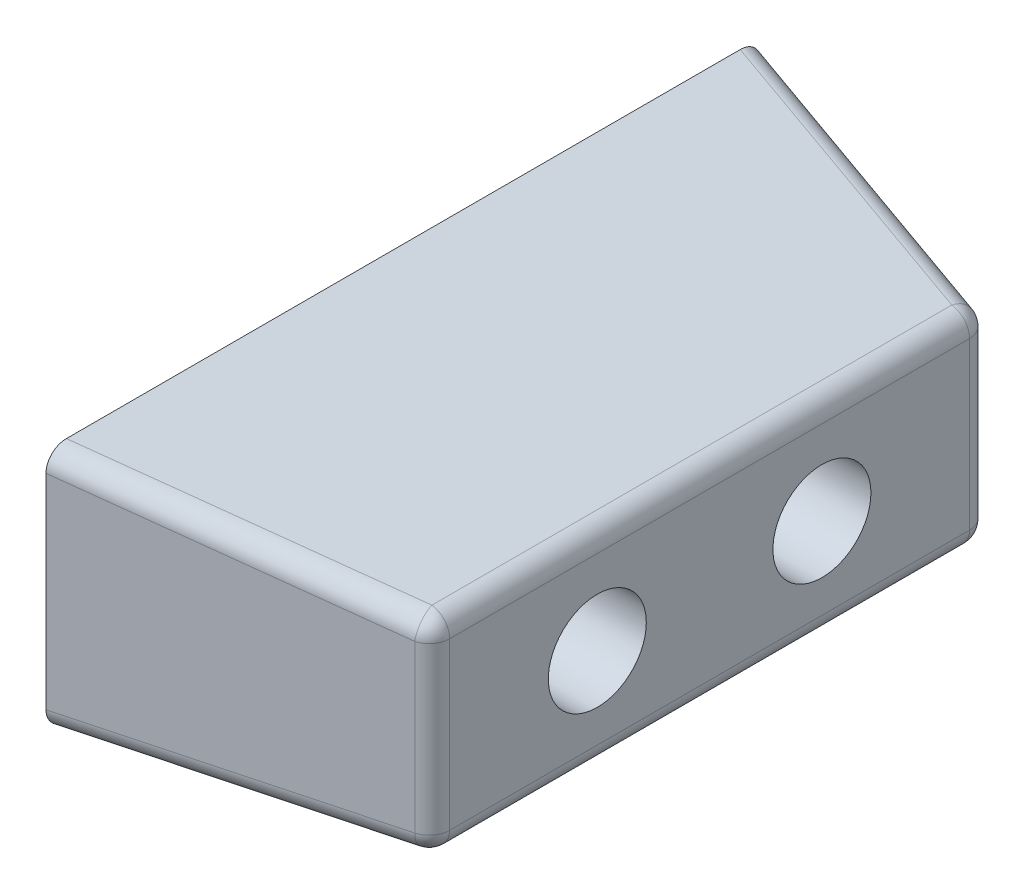
SolidWorks part; units mm, degrees
material "硅橡胶"
ref_plane "前视基准面" through (0, 0, 0) normal (0, 0, 1) x (1, 0, 0)
ref_plane "上视基准面" through (0, 0, 0) normal (0, 1, 0) x (1, 0, 0)
ref_plane "右视基准面" through (0, 0, 0) normal (1, 0, 0) x (0, 0, -1)
sketch "草图1" plane through (0, 0, 0) normal (0, 0, 1) x (1, 0, 0)
  line L0 (0, 0) -> (0, 60)
  line L1 (0, 0) -> (75, 0)
  line L2 (75, 0) -> (75, 50)
  line L3 (75, 50) -> (0, 60)
  dimension "D1" = 60
  dimension "D2" = 50
  dimension "D3" = 75
extrude "凸台-拉伸1" add sketch "草图1" along normal mid plane 175
sketch "草图2" plane through (0, 0, 0) normal (0, -1, 0) x (1, 0, 0)
  line L0 (0, 0) -> (75, 0) construction
  line L1 (75, 87.5) -> (75, -87.5) construction
  line L2 (0, 87.5) -> (75, 67.5)
  line L3 (0, -87.5) -> (75, -67.5)
  line L4 (0, -87.5) -> (75, -87.5) construction
  line L5 (0, -87.5) -> (75, -87.5)
  line L6 (75, 87.5) -> (75, 67.5)
  line L7 (0, 87.5) -> (75, 87.5) construction
  line L8 (0, 87.5) -> (75, 87.5)
  line L9 (75, -67.5) -> (75, -87.5)
  dimension "D1" = 135
extrude "切除-拉伸1" cut sketch "草图2" against normal blind 175
sketch "草图3" plane through (75, 0, 0) normal (1, 0, 0) x (0, 0, -1)
  line L0 (0, 0) -> (0, 50) construction
  line L2 (0, 25) -> (-27.5, 25) construction
  line L3 (-67.5, 50) -> (67.5, 50) construction
  circle A0 centre (-27.5, 25) radius 12
  circle A1 centre (27.5, 25) radius 12
  dimension "D1" = 24
  dimension "D2" = 55
extrude "切除-拉伸2" cut sketch "草图3" against normal blind 52
sketch "草图4" plane through (23, 0, 0) normal (1, 0, 0) x (0, 0, -1)
  circle A0 centre (-27.5, 25) radius 5.5
  circle A1 centre (27.5, 25) radius 5.5
  dimension "D1" = 11
extrude "切除-拉伸3" cut sketch "草图4" against normal blind 40
fillet "圆角1" radius 5 8 edges at (37.5, 55, -77.5) (37.5, 0, -77.5) (75, 25, -67.5) (75, 0, 0) (37.5, 0, 77.5) (75, 25, 67.5) (75, 50, 0) (37.5, 55, 77.5)
